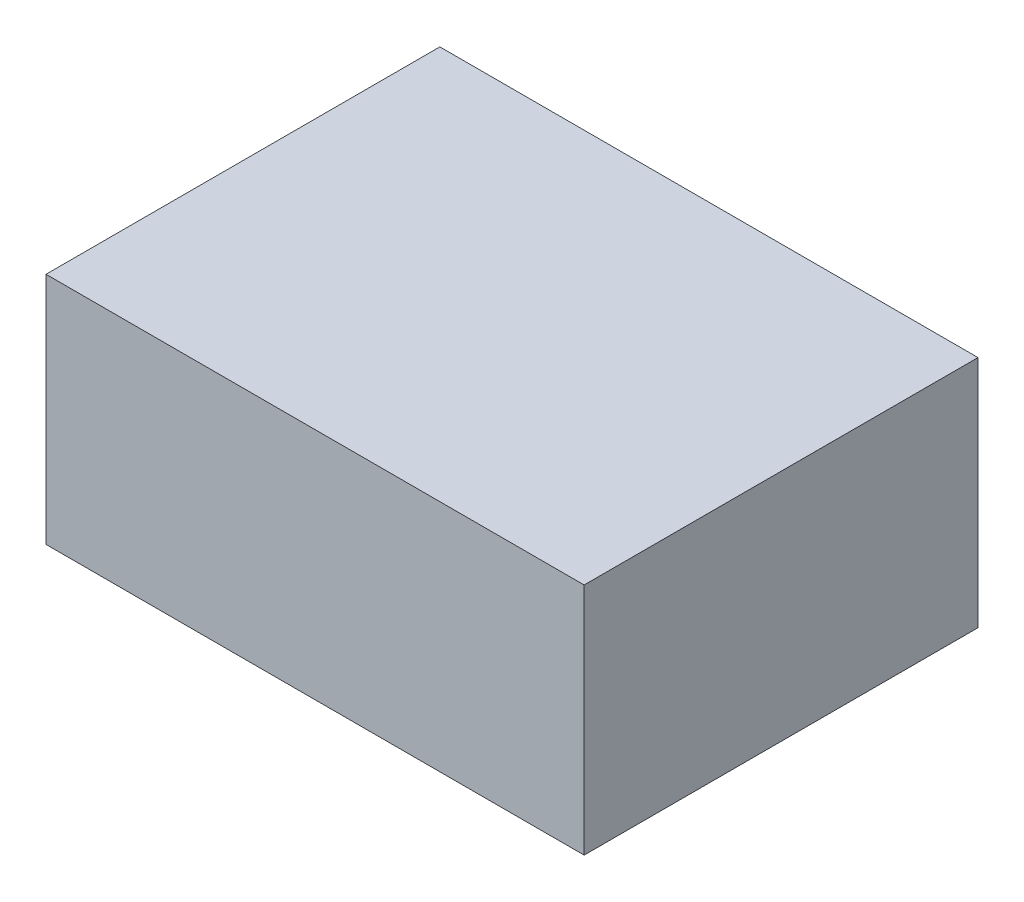
SolidWorks part; units mm, degrees
ref_plane "Front Plane" through (0, 0, 0) normal (0, 0, 1) x (1, 0, 0)
ref_plane "Top Plane" through (0, 0, 0) normal (0, 1, 0) x (1, 0, 0)
ref_plane "Right Plane" through (0, 0, 0) normal (1, 0, 0) x (0, 0, -1)
sketch "Sketch1" plane through (0, 0, 0) normal (0, 1, 0) x (1, 0, 0)
  line L1 (-3.45, -2.525) -> (3.45, -2.525)
  line L2 (-3.45, -2.525) -> (-3.45, 2.525)
  line L3 (-3.45, 2.525) -> (3.45, 2.525)
  line L4 (3.45, -2.525) -> (3.45, 2.525)
  line L5 (-3.45, -2.525) -> (3.45, 2.525) construction
  line L6 (-3.45, 2.525) -> (3.45, -2.525) construction
  point P0 (0, 0)
  dimension "D1" = 6.9
  dimension "D2" = 5.05
extrude "Boss-Extrude1" add sketch "Sketch1" along normal blind 3
